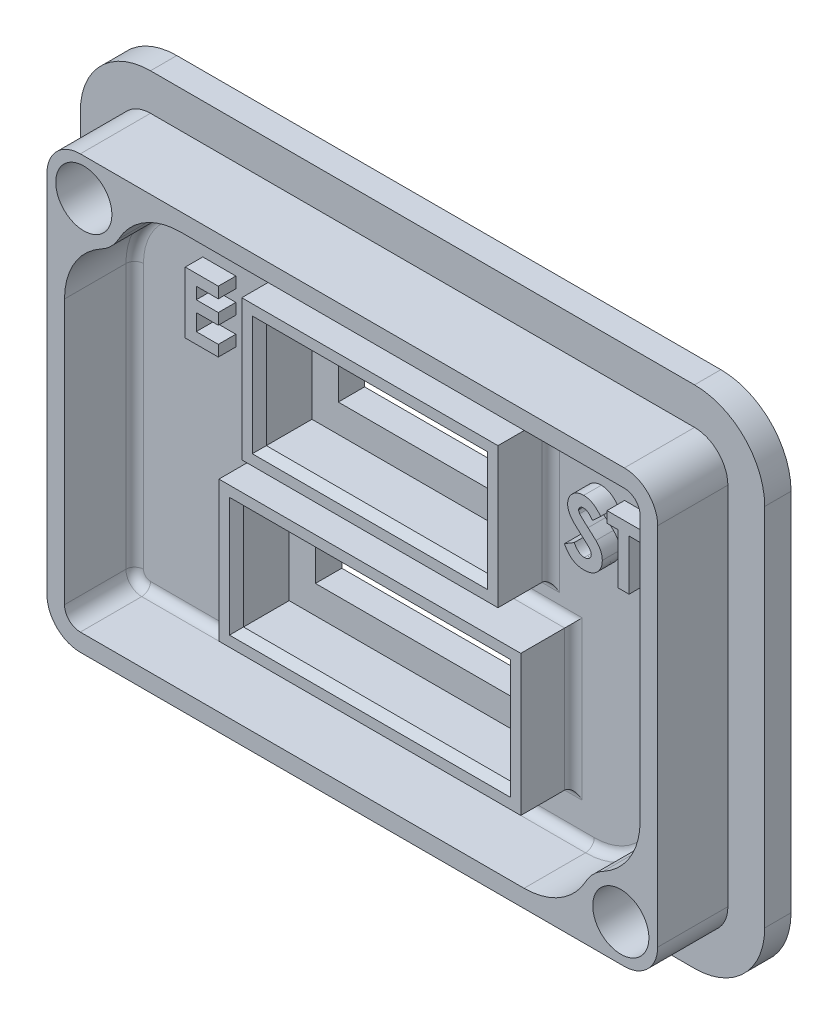
SolidWorks part; units mm, degrees
ref_plane "Ebene vorne" through (0, 0, 0) normal (0, 0, 1) x (1, 0, 0)
ref_plane "Ebene oben" through (0, 0, 0) normal (0, 1, 0) x (1, 0, 0)
ref_plane "Ebene rechts" through (0, 0, 0) normal (1, 0, 0) x (0, 0, -1)
sketch "Skizze1" plane through (0, 0, 0) normal (0, 0, 1) x (1, 0, 0)
  line L1 (15.5, -14.4) -> (-15.5, -14.4)
  line L2 (19.5, -10.4) -> (19.5, 10.4)
  line L3 (15.5, 14.4) -> (-15.5, 14.4)
  line L4 (-19.5, -10.4) -> (-19.5, 10.4)
  line L5 (19.5, -14.4) -> (-19.5, 14.4) construction
  line L6 (19.5, 14.4) -> (-19.5, -14.4) construction
  arc A0 (-15.5, -14.4) -> (-19.5, -10.4) centre (-15.5, -10.4) cw
  arc A1 (15.5, -14.4) -> (19.5, -10.4) centre (15.5, -10.4) ccw
  arc A2 (19.5, 10.4) -> (15.5, 14.4) centre (15.5, 10.4) ccw
  arc A3 (-15.5, 14.4) -> (-19.5, 10.4) centre (-15.5, 10.4) ccw
  point P0 (0, 0)
  dimension "D3" = 4
  dimension "D1" = 28.8
  dimension "D2" = 39
extrude "Aufsatz-Linear austragen1" add sketch "Skizze1" along normal blind 1.5
sketch "Skizze2" plane through (0, 0, 1.5) normal (0, 0, 1) x (1, 0, 0)
  line L0 (15.5, 11.3) -> (-9.7869, 11.3)
  line L1 (-16.4, 4.6869) -> (-16.4, -10.4)
  line L2 (-15.5, -11.3) -> (9.7869, -11.3)
  line L3 (16.4, -4.6869) -> (16.4, 10.4)
  line L4 (15.5, 11.3) -> (-15.5, 11.3) construction
  line L5 (-16.4, 10.4) -> (-16.4, -10.4) construction
  line L6 (15.5464, 10.4311) -> (-15.5464, -10.4311) construction
  line L7 (16.4, -10.4) -> (16.4, 10.4) construction
  line L8 (-15.5, -11.3) -> (15.5, -11.3) construction
  line L10 (-15.5, -12.3) -> (15.5, -12.3)
  line L11 (17.4, -10.4) -> (17.4, 10.4)
  line L12 (15.5, 12.3) -> (-15.5, 12.3)
  line L13 (-17.4, 10.4) -> (-17.4, -10.4)
  line L14 (-15.5, -12.3) -> (15.5, -12.3)
  line L15 (17.4, -10.4) -> (17.4, 10.4)
  line L16 (15.5, 12.3) -> (-15.5, 12.3)
  line L17 (-17.4, 10.4) -> (-17.4, -10.4)
  arc A1 (-16.4, -10.4) -> (-15.5, -11.3) centre (-15.5, -10.4) ccw
  arc A3 (16.4, 10.4) -> (15.5, 11.3) centre (15.5, 10.4) ccw
  arc A4 (-14.3077, 8.2026) -> (-13.3026, 9.2077) centre (-15.5, 10.4) ccw
  arc A5 (-14.3077, 8.2026) -> (-16.4, 4.6869) centre (-12.4, 4.6869) ccw
  arc A6 (-13.3026, 9.2077) -> (-9.7869, 11.3) centre (-9.7869, 7.3) cw
  circle A7 centre (-15.3, 10.2) radius 1.6
  arc A8 (14.3077, -8.2026) -> (13.3026, -9.2077) centre (15.5, -10.4) ccw
  arc A9 (14.3077, -8.2026) -> (16.4, -4.6869) centre (12.4, -4.6869) ccw
  arc A10 (13.3026, -9.2077) -> (9.7869, -11.3) centre (9.7869, -7.3) cw
  circle A11 centre (15.3, -10.2) radius 1.6
  arc A12 (-17.4, -10.4) -> (-15.5, -12.3) centre (-15.5, -10.4) ccw
  arc A13 (15.5, -12.3) -> (17.4, -10.4) centre (15.5, -10.4) ccw
  arc A14 (17.4, 10.4) -> (15.5, 12.3) centre (15.5, 10.4) ccw
  arc A15 (-15.5, 12.3) -> (-17.4, 10.4) centre (-15.5, 10.4) ccw
  arc A16 (-17.4, -10.4) -> (-15.5, -12.3) centre (-15.5, -10.4) ccw
  arc A17 (15.5, -12.3) -> (17.4, -10.4) centre (15.5, -10.4) ccw
  arc A18 (17.4, 10.4) -> (15.5, 12.3) centre (15.5, 10.4) ccw
  arc A19 (-15.5, 12.3) -> (-17.4, 10.4) centre (-15.5, 10.4) ccw
  arc A20 (-15.5, 11.3) -> (-16.4, 10.4) centre (-15.5, 10.4) ccw construction
  arc A21 (15.5, -11.3) -> (16.4, -10.4) centre (15.5, -10.4) ccw construction
  dimension "D3" = 5
  dimension "D4" = 4
  dimension "D5" = 3.2
  dimension "D6" = 5
  dimension "D7" = 4
  dimension "D10" = 3.2
  dimension "D8" = 2.1
  dimension "D9" = 2.1
  dimension "D11" = 2.1
  dimension "D12" = 2.1
  dimension "D1" = 2.1
  dimension "D2" = 1
extrude "Aufsatz-Linear austragen2" add sketch "Skizze2" along normal blind 4
sketch "Skizze3" plane through (0, 0, 1.5) normal (0, 0, 1) x (1, 0, 0)
  line L0 (0, 11.4) -> (0, -2.7562) construction
  line L1 (8.6, -0.8) -> (-8.6, -0.8)
  line L2 (7.3, 8.8) -> (-7.3, 8.8)
  line L3 (6.3, 1.8) -> (-6.3, 1.8)
  line L4 (6.3, 1.8) -> (6.3, 7.8)
  line L5 (6.3, 7.8) -> (-6.3, 7.8)
  line L6 (-6.3, 1.8) -> (-6.3, 7.8)
  line L7 (6.3, 1.8) -> (-6.3, 7.8) construction
  line L8 (6.3, 7.8) -> (-6.3, 1.8) construction
  line L9 (7.6, -7.8) -> (-7.6, -7.8)
  line L10 (7.6, -7.8) -> (7.6, -1.8)
  line L11 (7.6, -1.8) -> (-7.6, -1.8)
  line L12 (-7.6, -7.8) -> (-7.6, -1.8)
  line L13 (7.6, -7.8) -> (-7.6, -1.8) construction
  line L14 (7.6, -1.8) -> (-7.6, -7.8) construction
  line L15 (-7.3, 0.8) -> (-7.3, 8.8)
  line L16 (7.3, 0.8) -> (-7.3, 0.8)
  line L17 (7.3, 0.8) -> (7.3, 8.8)
  line L18 (-8.6, -8.8) -> (-8.6, -0.8)
  line L19 (8.6, -8.8) -> (-8.6, -8.8)
  line L20 (8.6, -8.8) -> (8.6, -0.8)
  line L21 (15.5, 11.3) -> (-9.7869, 11.3) construction
  line L22 (-15.5, -11.3) -> (9.7869, -11.3) construction
  point P1 (0, 4.8)
  point P8 (0, -4.8)
  dimension "D1" = 6
  dimension "D2" = 12.6
  dimension "D3" = 6
  dimension "D4" = 15.2
  dimension "D7" = 2.5
  dimension "D8" = 2.5
  dimension "D5" = 1
  dimension "D6" = 1
extrude "Aufsatz-Linear austragen3" add sketch "Skizze3" along normal blind 3
sketch "Skizze4" plane through (0, 0, 1.5) normal (0, 0, 1) x (1, 0, 0)
  line L1 (4.8, 3.4) -> (-4.8, 3.4)
  line L2 (4.8, 3.4) -> (4.8, 5.4)
  line L3 (4.8, 5.4) -> (-4.8, 5.4)
  line L4 (-4.8, 3.4) -> (-4.8, 5.4)
  line L5 (4.8, 3.4) -> (-4.8, 5.4) construction
  line L6 (4.8, 5.4) -> (-4.8, 3.4) construction
  line L7 (6.3, 7.8) -> (-6.3, 7.8) construction
  line L9 (6.1, -6.2) -> (-6.1, -6.2)
  line L10 (6.1, -6.2) -> (6.1, -4.2)
  line L11 (6.1, -4.2) -> (-6.1, -4.2)
  line L12 (-6.1, -6.2) -> (-6.1, -4.2)
  line L13 (6.1, -6.2) -> (-6.1, -4.2) construction
  line L14 (6.1, -4.2) -> (-6.1, -6.2) construction
  line L15 (-6.3, 7.8) -> (-6.3, 1.8) construction
  line L16 (6.3, 1.8) -> (6.3, 7.8) construction
  line L17 (-7.6, -1.8) -> (-7.6, -7.8) construction
  line L18 (7.6, -7.8) -> (7.6, -1.8) construction
  line L19 (7.6, -1.8) -> (-7.6, -1.8) construction
  point P6 (0, 4.4)
  point P11 (0, -5.2)
  dimension "D1" = 2
  dimension "D2" = 1.5
  dimension "D3" = 3.4
  dimension "D4" = 2
  dimension "D5" = 1.5
  dimension "D6" = 1.5
  dimension "D7" = 1.5
  dimension "D8" = 3.4
extrude "Schnitt-Linear austragen1" cut sketch "Skizze4" against normal through all
fillet "Verrundung1" radius 0.5 20 edges at (16.1364, 11.0364, 1.5) (16.4, 2.8566, 1.5) (15.8374, -6.7325, 1.5) (13.7322, -8.6322, 1.5) (11.8325, -10.7374, 1.5) (-2.8566, -11.3, 1.5) (-16.1364, -11.0364, 1.5) (-16.4, -2.8566, 1.5) (-15.8374, 6.7325, 1.5) (-13.7322, 8.6322, 1.5) (-11.8325, 10.7374, 1.5) (2.8566, 11.3, 1.5) (0, -0.8, 1.5) (0, -8.8, 1.5) (8.6, -4.8, 1.5) (-8.6, -4.8, 1.5) (0, 8.8, 1.5) (7.3, 4.8, 1.5) (-7.3, 4.8, 1.5) (0, 0.8, 1.5)
chamfer "Fase1" distance 0.4 angle 45 8 edges at (7.6, -4.8, 4.5) (0, -7.8, 4.5) (-7.6, -4.8, 4.5) (0, -1.8, 4.5) (6.3, 4.8, 4.5) (0, 1.8, 4.5) (-6.3, 4.8, 4.5) (0, 7.8, 4.5)
sketch "Skizze5" plane through (0, 0, 1.5) normal (0, 0, 1) x (1, 0, 0)
  line L0 (-12.9246, 3.2018) -> (13.4428, 3.2018) construction
  text T0 "<b>E</b>"
  text T1 "<b>ST</b>"
extrude "Aufsatz-Linear austragen4" add sketch "Skizze5" along normal blind 1
sketch "Skizze6" plane through (0, 0, 1.5) normal (0, 0, 1) x (1, 0, 0)
  circle A0 centre (15.3, -10.2) radius 1.6 construction
  circle A1 centre (-15.3, 10.2) radius 1.6 construction
  circle A2 centre (15.3, -10.2) radius 1.6
  circle A3 centre (-15.3, 10.2) radius 1.6
extrude "Schnitt-Linear austragen2" cut sketch "Skizze6" against normal blind 0.6
equation "\"D10@Skizze2\"=\"D5@Skizze2\""
